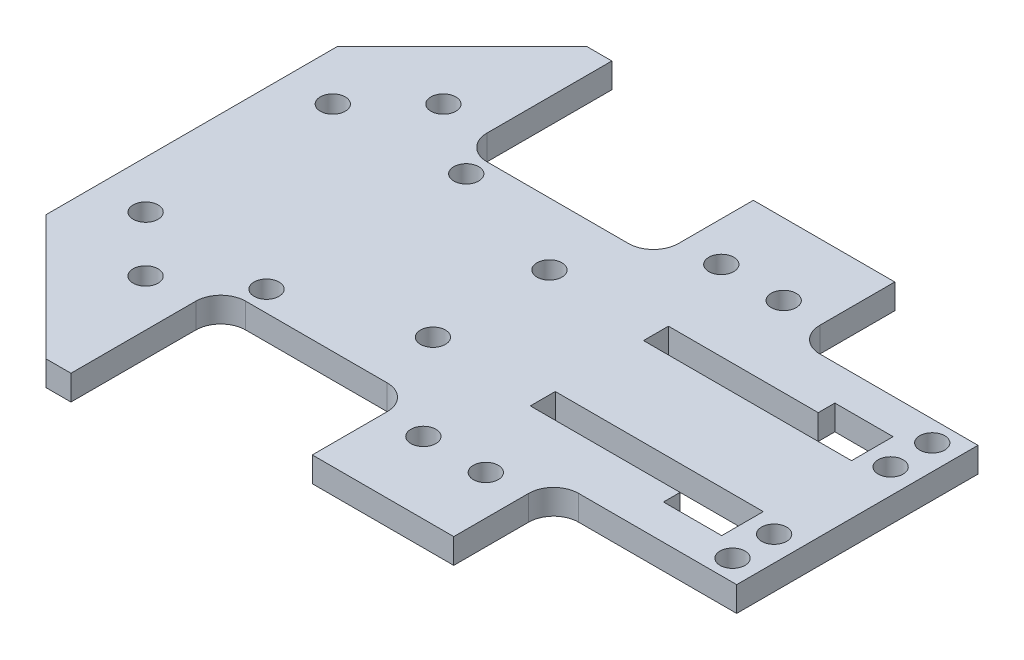
SolidWorks part; units mm, degrees
ref_plane "Front Plane" through (0, 0, 0) normal (0, 0, 1) x (1, 0, 0)
ref_plane "Top Plane" through (0, 0, 0) normal (0, 1, 0) x (1, 0, 0)
ref_plane "Right Plane" through (0, 0, 0) normal (1, 0, 0) x (0, 0, -1)
sketch "Sketch1" plane through (0, 0, 0) normal (0, 1, 0) x (1, 0, 0)
  line L1 (-40, -32.5) -> (40, -32.5)
  line L2 (-40, -32.5) -> (-40, 32.5)
  line L3 (-40, 32.5) -> (40, 32.5)
  line L4 (40, -32.5) -> (40, 32.5)
  line L5 (-40, -32.5) -> (40, 32.5) construction
  line L6 (-40, 32.5) -> (40, -32.5) construction
  point P0 (0, 0)
  dimension "D1" = 80
  dimension "D2" = 65
extrude "Boss-Extrude1" add sketch "Sketch1" along normal blind 3
sketch "Sketch2" plane through (0, 0, 0) normal (0, -1, 0) x (-1, 0, 0)
  line L0 (22, 32.5) -> (22, 14.5)
  line L1 (22, 32.5) -> (-40, 32.5)
  line L2 (-1, -26.5) -> (-18, -26.5)
  line L3 (-18, -14.5) -> (-40, -14.5)
  line L4 (-18, -26.5) -> (-18, -14.5)
  line L5 (-40, 32.5) -> (40, 32.5) construction
  line L6 (22, 14.5) -> (-1, 14.5)
  line L7 (-40, -32.5) -> (-40, 32.5) construction
  line L8 (-40, 14.5) -> (-40, 32.5)
  line L10 (40, 0) -> (-40, 0) construction
  line L11 (40, 32.5) -> (40, -32.5) construction
  line L12 (-1, 26.5) -> (-1, 14.5)
  line L15 (-18, 26.5) -> (-18, 14.5)
  line L16 (-18, 14.5) -> (-40, 14.5)
  line L17 (-1, 26.5) -> (-18, 26.5)
  line L29 (-1, -26.5) -> (-1, -14.5)
  line L30 (-40, -14.5) -> (-40, -32.5)
  line L31 (22, -14.5) -> (-1, -14.5)
  line L32 (22, -32.5) -> (-40, -32.5)
  line L33 (22, -32.5) -> (22, -14.5)
  dimension "D1" = 22
  dimension "D2" = 62
  dimension "D4" = 6
  dimension "D5" = 17
  dimension "D6" = 18
extrude "Cut-Extrude1" cut sketch "Sketch2" against normal blind 10
sketch "Sketch3" plane through (0, 3, 0) normal (0, 1, 0) x (1, 0, 0)
  line L0 (-40, 0) -> (40, 0) construction
  line L1 (-40, 32.5) -> (-40, -32.5) construction
  line L2 (40, -14.5) -> (40, 14.5) construction
  line L7 (27, -8.3) -> (9, -8.3)
  line L8 (34, 5.3) -> (34, 10.3)
  line L9 (9, 5.3) -> (34, 5.3)
  line L10 (9, 8.3) -> (9, 5.3)
  line L11 (34, 10.3) -> (27, 10.3)
  line L12 (27, 8.3) -> (27, 10.3)
  line L13 (27, 8.3) -> (9, 8.3)
  line L14 (40, 14.5) -> (18, 14.5) construction
  line L15 (27, -8.3) -> (27, -10.3)
  line L16 (34, -10.3) -> (27, -10.3)
  line L17 (9, -8.3) -> (9, -5.3)
  line L18 (9, -5.3) -> (34, -5.3)
  line L19 (34, -5.3) -> (34, -10.3)
  dimension "D1" = 6
  dimension "D2" = 4.2
  dimension "D3" = 5
  dimension "D4" = 2
  dimension "D5" = 25
  dimension "D6" = 18
extrude "Cut-Extrude2" cut sketch "Sketch3" against normal blind 10
sketch "Sketch4" plane through (0, 3, 0) normal (0, 1, 0) x (1, 0, 0)
  circle A0 centre (-4, 7) radius 1.5
  circle A1 centre (13.25, 17.9) radius 1.5
  circle A2 centre (5.75, 17.9) radius 1.5
  circle A3 centre (37, 7) radius 1.5
  circle A4 centre (37, 12) radius 1.5
  circle A5 centre (-19, 12) radius 1.5
  circle A6 centre (-27.6368, 17.8927) radius 1.5
  circle A7 centre (-34.2836, 11.2459) radius 1.5
  circle A8 centre (-34.2836, -11.2459) radius 1.5
  circle A9 centre (-27.6368, -17.8927) radius 1.5
  circle A10 centre (-19, -12) radius 1.5
  circle A11 centre (-4, -7) radius 1.5
  circle A12 centre (5.75, -17.9) radius 1.5
  circle A13 centre (13.25, -17.9) radius 1.5
  circle A14 centre (37, -7) radius 1.5
  circle A16 centre (37, -12) radius 1.5
  dimension "D1" = 3
extrude "Cut-Extrude3" cut sketch "Sketch4" against normal blind 10
fillet "Fillet1" radius 3 6 edges at (18, 1.5, -14.5) (18, 1.5, 14.5) (1, 1.5, 14.5) (-22, 1.5, 14.5) (1, 1.5, -14.5) (-22, 1.5, -14.5)
sketch "Sketch5" plane through (0, 0, 0) normal (0, -1, 0) x (-1, 0, 0)
  line L0 (40, 32.5) -> (25, 32.5)
  line L1 (25, 32.5) -> (40, 17.5)
  line L2 (40, 32.5) -> (40, -32.5) construction
  line L3 (40, 17.5) -> (40, 32.5)
  line L4 (40, 0) -> (0, 0) construction
  line L5 (40, -17.5) -> (40, -32.5)
  line L6 (25, -32.5) -> (40, -17.5)
  line L7 (40, -32.5) -> (25, -32.5)
  dimension "D1" = 15
  dimension "D2" = 15
extrude "Cut-Extrude4" cut sketch "Sketch5" against normal blind 10
